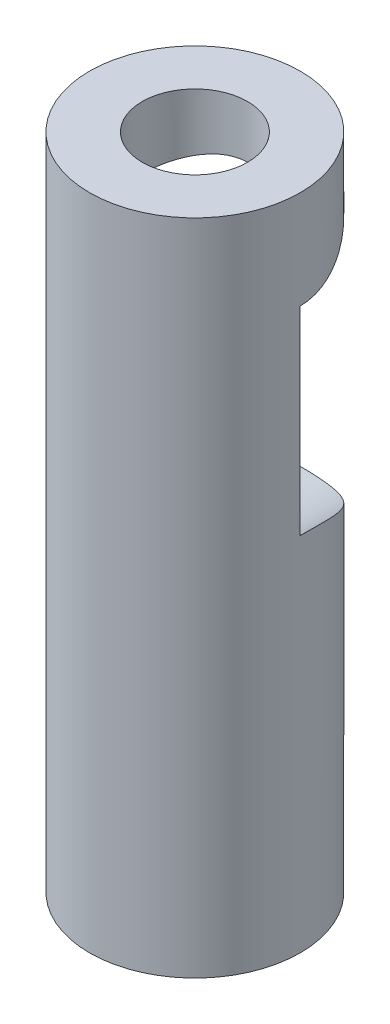
SolidWorks part; units mm, degrees
ref_plane "Plan de face" through (0, 0, 0) normal (0, 0, 1) x (1, 0, 0)
ref_plane "Plan de dessus" through (0, 0, 0) normal (0, 1, 0) x (1, 0, 0)
ref_plane "Plan de droite" through (0, 0, 0) normal (1, 0, 0) x (0, 0, -1)
sketch "Esquisse1" plane through (0, 0, 0) normal (0, 1, 0) x (1, 0, 0)
  circle A0 centre (0, 0) radius 4
  circle A1 centre (0, 0) radius 8
  dimension "D1" = 8
  dimension "D2" = 16
extrude "Boss.-Extru.1" add sketch "Esquisse1" along normal blind 30
sketch "Esquisse2" plane through (0, 0, 0) normal (0, 0, 1) x (1, 0, 0)
  line L0 (0, 0) -> (0, 15) construction
  circle A0 centre (0, 15) radius 11
  point P6 (-14.9777, 6.9464)
  dimension "D1" = 22
  dimension "D2" = 15
extrude "Enlèv. mat.-Extru.1" cut sketch "Esquisse2" against normal through all contours A0
sketch "Esquisse3" plane through (0, 0, 0) normal (0, -1, 0) x (1, 0, 0)
  circle A0 centre (0, 0) radius 4
  circle A1 centre (0, 0) radius 8
extrude "Boss.-Extru.2" add sketch "Esquisse3" along normal blind 20
